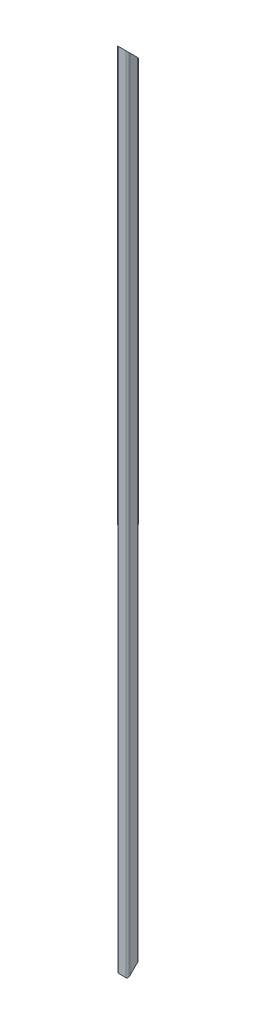
SolidWorks part; units mm, degrees
ref_plane "Спереди" through (0, 0, 0) normal (0, 0, 1) x (1, 0, 0)
ref_plane "Сверху" through (0, 0, 0) normal (0, 1, 0) x (1, 0, 0)
ref_plane "Справа" through (0, 0, 0) normal (1, 0, 0) x (0, 0, -1)
sketch "Эскиз1" plane through (0, 0, 0) normal (0, 1, 0) x (1, 0, 0)
  line L1 (-20, 30) -> (20, 30)
  line L2 (-30, 20) -> (-30, -20)
  line L3 (-20, -30) -> (20, -30)
  line L4 (30, 20) -> (30, -20)
  line L5 (-30, 30) -> (30, -30) construction
  line L6 (-30, -30) -> (30, 30) construction
  line L7 (-16, 26) -> (16, 26)
  line L8 (-26, 16) -> (-26, -16)
  line L9 (-16, -26) -> (16, -26)
  line L10 (26, 16) -> (26, -16)
  line L11 (-26, 26) -> (26, -26) construction
  line L12 (-26, -26) -> (26, 26) construction
  arc A0 (20, 30) -> (30, 20) centre (20, 20) cw
  arc A1 (-20, 30) -> (-30, 20) centre (-20, 20) ccw
  arc A2 (-30, -20) -> (-20, -30) centre (-20, -20) ccw
  arc A3 (20, -30) -> (30, -20) centre (20, -20) ccw
  arc A4 (16, -26) -> (26, -16) centre (16, -16) ccw
  arc A5 (16, 26) -> (26, 16) centre (16, 16) cw
  arc A6 (-16, 26) -> (-26, 16) centre (-16, 16) ccw
  arc A7 (-26, -16) -> (-16, -26) centre (-16, -16) ccw
  point P0 (0, 0)
  point P6 (0, 0)
  dimension "D5" = 10
  dimension "D1" = 60
  dimension "D2" = 60
  dimension "D3" = 4
  dimension "D4" = 4
extrude "Бобышка-Вытянуть1" add sketch "Эскиз1" along normal blind 4240
sketch "Эскиз2" plane through (30, 0, 0) normal (1, 0, 0) x (0, 0, -1)
  line L0 (-30, 0) -> (30, 0)
  line L1 (30, 0) -> (30, 60)
  line L2 (30, 4240) -> (30, 0) construction
  line L3 (30, 60) -> (-30, 0)
  line L4 (-30, 4240) -> (30, 4240)
  line L5 (30, 4240) -> (30, 4180)
  line L6 (30, 4180) -> (-30, 4240)
  dimension "D1" = 45
  dimension "D2" = 45
extrude "Вырез-Вытянуть1" cut sketch "Эскиз2" against normal through all
